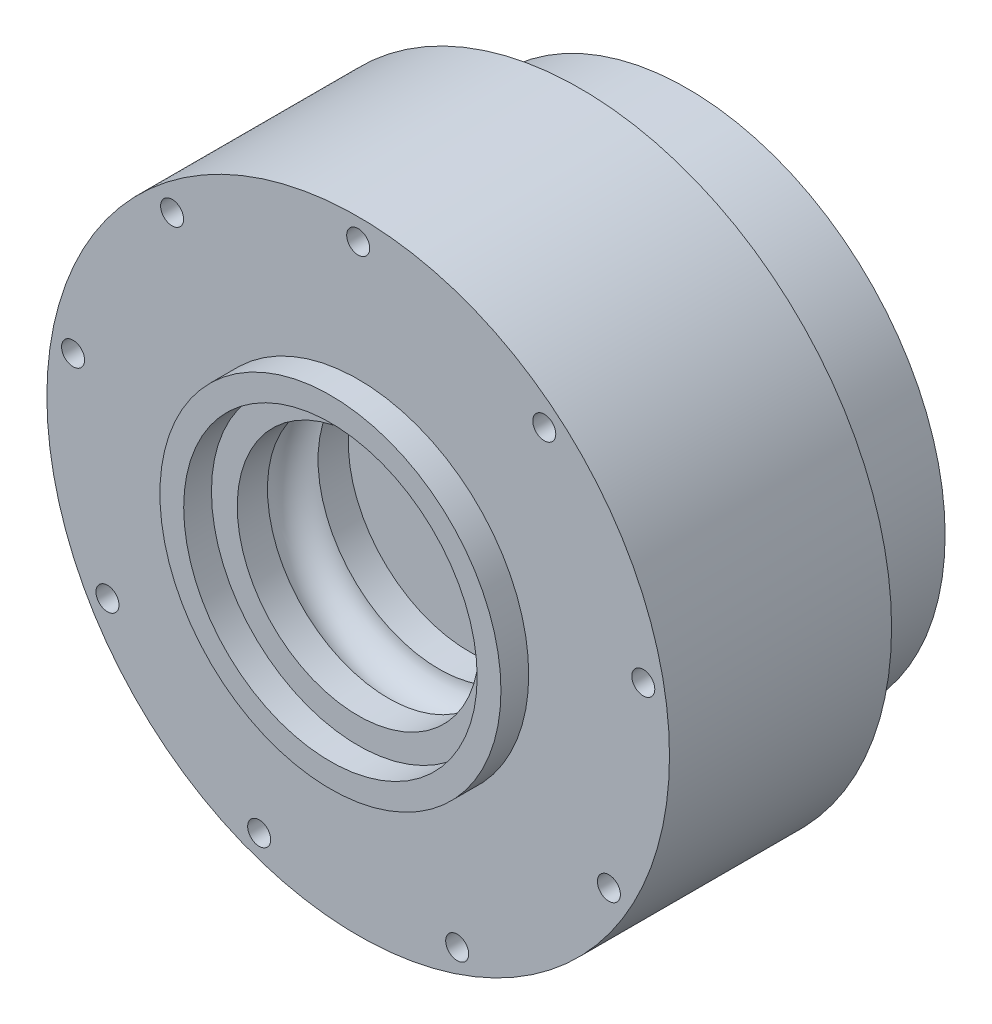
SolidWorks part; units mm, degrees
ref_plane "Front Plane" through (0, 0, 0) normal (0, 0, 1) x (1, 0, 0)
ref_plane "Top Plane" through (0, 0, 0) normal (0, 1, 0) x (1, 0, 0)
ref_plane "Right Plane" through (0, 0, 0) normal (1, 0, 0) x (0, 0, -1)
sketch "Sketch1" plane through (0, 0, 0) normal (1, 0, 0) x (0, 0, -1)
  line L0 (-51.2337, 0) -> (53.235, 0) construction
  line L2 (-31.5, 21.5) -> (-28, 21.5)
  line L3 (-28, 21.5) -> (-28, 39.25)
  line L4 (-28, 39.25) -> (0, 39.25)
  line L5 (0, 39.25) -> (0, 32.5)
  line L6 (0, 32.5) -> (13.5, 32.5)
  line L7 (13.5, 32.5) -> (13.5, 0)
  line L8 (13.5, 0) -> (-32, 0)
  line L9 (0, 0) -> (0, 68.8453) construction
  line L10 (-31.5, 21.5) -> (-31.5, 18.5)
  line L11 (-31.5, 18.5) -> (-28, 18.5)
  line L12 (-28, 18.5) -> (-28, 15)
  line L13 (-28, 15) -> (-32, 15)
  line L14 (-32, 15) -> (-32, 0)
  dimension "D1" = 43
  dimension "D2" = 28
  dimension "D3" = 41.5
  dimension "D4" = 65
  dimension "D5" = 3.5
  dimension "D6" = 78.5
  dimension "D7" = 0.5
  dimension "D8" = 30
  dimension "D9" = 3
revolve "Revolve1" [suppressed] add sketch "Sketch1" angle 360 about L0
sketch "Sketch2" [suppressed] plane through (0, 0, 28) normal (0, 0, 1) x (1, 0, 0)
  circle A0 centre (0, 0) radius 36.5 construction
  point P3 (0, 36.5)
  point P4 (0, 36.5)
  point P11 (23.4617, 27.9606)
  point P12 (35.9455, 6.3382)
  point P13 (31.6099, -18.25)
  point P14 (12.4837, -34.2988)
  point P15 (-12.4837, -34.2988)
  point P16 (-31.6099, -18.25)
  point P17 (-35.9455, 6.3382)
  point P18 (-23.4617, 27.9606)
  dimension "D1" = 73
  dimension "D2" = 9
hole_wizard "Ø3.0mm Dowel Hole1" [suppressed] positions "Sketch2" profile "Sketch3" hole size "Ø3.0" standard "ANSI Metric"
sketch "Sketch3" plane through (-23.4617, 27.9606, 28) normal (1, 0, 0) x (0, -1, 0)
  line L0 (0, 0) -> (0, 8.9013)
  line L1 (0, 8.9013) -> (1.5, 8)
  line L2 (1.5, 8) -> (1.5, 0)
  line L5 (1.5, 0) -> (0, 0)
  line L10 (0, 8.9013) -> (-1.5, 8) construction
  line L11 (0, -6.35) -> (0, 107.95) construction
  dimension "Hole Dia." = 3
  dimension "Hole Depth" = 8
  dimension "Drill Angle" = 118
hole_wizard "Ø3.0mm Dowel Hole2" [suppressed] positions "Sketch4" profile "Sketch6" hole size "Ø3.0" standard "ANSI Metric"
sketch "Sketch4" [suppressed] plane through (0, 0, 28) normal (0, 0, 1) x (1, 0, 0)
  line L0 (-12.4837, -34.2988) -> (12.4837, 34.2988) construction
  circle A0 centre (0, 0) radius 36.5 construction
  point P7 (12.4837, 34.2988)
  point P18 (23.4617, -27.9606)
  point P19 (-35.9455, -6.3382)
  dimension "D1" = 73
  dimension "D2" = 3
sketch "Sketch6" plane through (-35.9455, -6.3382, 28) normal (1, 0, 0) x (0, -1, 0)
  line L0 (0, 0) -> (0, 41.5)
  line L1 (0, 41.5) -> (1.5, 41.5)
  line L2 (1.5, 41.5) -> (1.5, 0)
  line L5 (1.5, 0) -> (0, 0)
  line L11 (0, -6.35) -> (0, 107.95) construction
  dimension "Thru Hole Dia." = 3
  dimension "Thru Hole Depth" = 41.5
hole_wizard "Ø4.0mm Dowel Hole1" [suppressed] positions "Sketch7" profile "Sketch8" hole size "Ø4.0" standard "ANSI Metric"
sketch "Sketch7" [suppressed] plane through (0, 0, 32) normal (0, 0, 1) x (1, 0, 0)
  circle A0 centre (0, 0) radius 12 construction
  point P6 (12, 0)
  point P14 (6, -10.3923)
  point P15 (-6, -10.3923)
  point P16 (-12, 0)
  point P17 (-6, 10.3923)
  point P18 (6, 10.3923)
  dimension "D1" = 24
  dimension "D2" = 6
sketch "Sketch8" plane through (6, 10.3923, 32) normal (1, 0, 0) x (0, -1, 0)
  line L0 (0, 0) -> (0, 8.2017)
  line L1 (0, 8.2017) -> (2, 7)
  line L2 (2, 7) -> (2, 0)
  line L5 (2, 0) -> (0, 0)
  line L10 (0, 8.2017) -> (-2, 7) construction
  line L11 (0, -6.35) -> (0, 107.95) construction
  dimension "Hole Dia." = 4
  dimension "Hole Depth" = 7
  dimension "Drill Angle" = 118
hole_wizard "Ø4.0mm Dowel Hole2" [suppressed] positions "Sketch9" profile "Sketch11" hole size "Ø4.0" standard "ANSI Metric"
sketch "Sketch9" [suppressed] plane through (0, 0, 32) normal (0, 0, 1) x (1, 0, 0)
  circle A0 centre (0, 0) radius 12 construction
  point P5 (0, 12)
  point P12 (10.3923, -6)
  point P13 (-10.3923, -6)
  dimension "D1" = 24
  dimension "D2" = 3
sketch "Sketch11" plane through (-10.3923, -6, 32) normal (1, 0, 0) x (0, -1, 0)
  line L0 (0, 0) -> (0, 45.5)
  line L1 (0, 45.5) -> (2, 45.5)
  line L2 (2, 45.5) -> (2, 0)
  line L5 (2, 0) -> (0, 0)
  line L11 (0, -6.35) -> (0, 107.95) construction
  dimension "Thru Hole Dia." = 4
  dimension "Thru Hole Depth" = 45.5
sketch "Sketch12" plane through (0, 0, 0) normal (1, 0, 0) x (0, 0, -1)
  line L0 (-41.1487, 0) -> (39.6006, 0) construction
  line L1 (-31.5, 21.5) -> (-28, 21.5)
  line L2 (-28, 21.5) -> (-28, 39.25)
  line L3 (-28, 39.25) -> (0, 39.25)
  line L4 (0, 39.25) -> (0, 32.5)
  line L5 (0, 32.5) -> (13.5, 32.5)
  line L6 (13.5, 32.5) -> (13.5, 0)
  line L7 (13.5, 0) -> (-14, 0)
  line L8 (0, 0) -> (0, 69.2827) construction
  line L9 (-31.5, 21.5) -> (-31.5, 18.5)
  line L10 (-31.5, 18.5) -> (-28, 18.5)
  line L11 (-28, 18.5) -> (-28, 15.25)
  line L14 (-28, 15.25) -> (-24.1902, 15.25)
  line L15 (-14, 15.25) -> (-14, 0)
  line L16 (-17.8098, 15.25) -> (-14, 15.25)
  arc A0 (-17.8098, 15.25) -> (-24.1902, 15.25) centre (-21, 15) ccw
  dimension "D6" = 78.5
  dimension "D9" = 6.4
  dimension "D1" = 28
  dimension "D2" = 41.5
  dimension "D3" = 3.5
  dimension "D4" = 43
  dimension "D5" = 65
  dimension "D10" = 14
  dimension "D7" = 30.5
  dimension "D11" = 7
  dimension "D12" = 30
revolve "Revolve2" add sketch "Sketch12" angle 360 about L0
hole_wizard "Ø3.0mm Dowel Hole3" positions "Sketch13" profile "Sketch14" hole size "Ø3.0" standard "ANSI Metric" end condition through all
sketch "Sketch13" plane through (0, 0, 28) normal (0, 0, 1) x (1, 0, 0)
  circle A0 centre (0, 0) radius 36.5 construction
  point P6 (0, 36.5)
  point P13 (23.4617, 27.9606)
  point P14 (35.9455, 6.3382)
  point P15 (31.6099, -18.25)
  point P16 (12.4837, -34.2988)
  point P17 (-12.4837, -34.2988)
  point P18 (-31.6099, -18.25)
  point P19 (-35.9455, 6.3382)
  point P20 (-23.4617, 27.9606)
  dimension "D1" = 73
  dimension "D2" = 9
sketch "Sketch14" plane through (-23.4617, 27.9606, 28) normal (1, 0, 0) x (0, -1, 0)
  line L0 (0, 0) -> (0, 41.5)
  line L1 (0, 41.5) -> (1.45, 41.5)
  line L2 (1.45, 41.5) -> (1.45, 0)
  line L5 (1.45, 0) -> (0, 0)
  line L11 (0, -6.35) -> (0, 107.95) construction
  dimension "Thru Hole Dia." = 2.9
  dimension "Thru Hole Depth" = 41.5
sketch "Sketch15" plane through (0, 0, 28) normal (0, 0, 1) x (1, 0, 0)
  line L0 (0, 0) -> (0, 61.703) construction
  circle A0 centre (0, 15) radius 3.2
  dimension "D2" = 6.4
  dimension "D1" = 15
extrude "Cut-Extrude1" cut sketch "Sketch15" against normal blind 6 and the other way through all
equation "\"D1\"= 78.5mm'Outer Diameters"
equation "\"D2\"= 43mm'Output Dieameters"
equation "\"D3\"= 65mm'Motor Driver Diameters"
equation "\"D1@Sketch1\"=\"D2\""
equation "\"D6@Sketch1\"=\"D1\""
equation "\"D4@Sketch1\"=\"D3\""
equation "\"D7@Sketch12\"=30.00mm+0.5mm"
